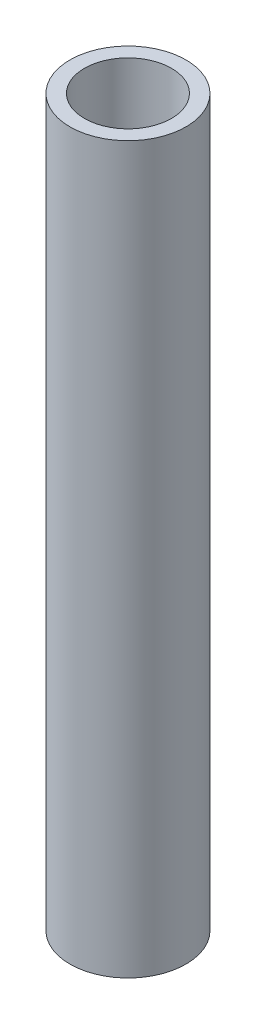
SolidWorks part; units mm, degrees
ref_plane "Front" through (0, 0, 0) normal (0, 0, 1) x (1, 0, 0)
ref_plane "Top" through (0, 0, 0) normal (0, 1, 0) x (1, 0, 0)
ref_plane "Right" through (0, 0, 0) normal (1, 0, 0) x (0, 0, -1)
sketch "Esquisse1" plane through (0, 0, 0) normal (0, 1, 0) x (1, 0, 0)
  circle A0 centre (0, 0) radius 4
  circle A1 centre (0, 0) radius 3
  dimension "D1" = 6
  dimension "D2" = 1
  dimension "D3" = 8
extrude "Boss.-Extru.1" add sketch "Esquisse1" along normal blind 9 and the other way blind 41
